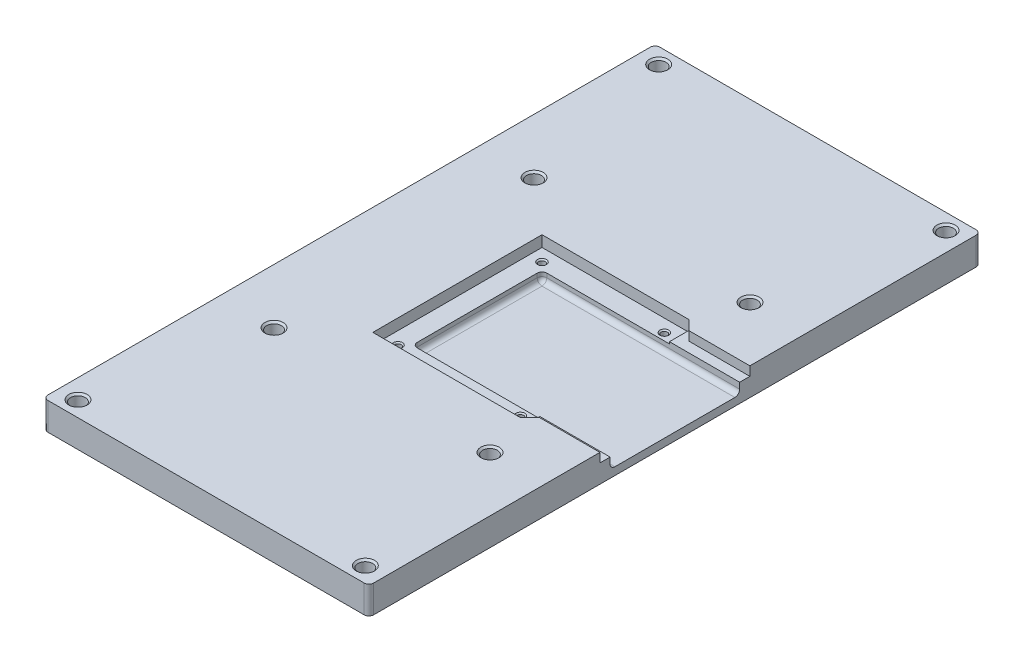
SolidWorks part; units mm, degrees
ref_plane "Front Plane" through (0, 0, 0) normal (0, 0, 1) x (1, 0, 0)
ref_plane "Top Plane" through (0, 0, 0) normal (0, 1, 0) x (1, 0, 0)
ref_plane "Right Plane" through (0, 0, 0) normal (1, 0, 0) x (0, 0, -1)
sketch "Sketch1" plane through (0, 0, 0) normal (0, 1, 0) x (1, 0, 0)
  line L0 (0, -112.5) -> (0, 112.5) construction
  line L1 (67.875, 112.5) -> (-67.875, 112.5) construction
  line L2 (-67.875, 112.5) -> (-67.875, -112.5)
  line L3 (-67.875, 0) -> (67.875, 0) construction
  line L4 (-67.875, 112.5) -> (-67.875, 125.5)
  line L5 (-65.875, 127.5) -> (65.875, 127.5)
  line L6 (0, 127.5) -> (0, 112.5) construction
  line L7 (67.875, 112.5) -> (67.875, 125.5)
  line L8 (67.875, 112.5) -> (67.875, -112.5)
  line L9 (0, -127.5) -> (0, -112.5) construction
  line L10 (67.875, -112.5) -> (-67.875, -112.5) construction
  line L11 (67.875, -112.5) -> (67.875, -125.5)
  line L12 (-65.875, -127.5) -> (65.875, -127.5)
  line L13 (-67.875, -112.5) -> (-67.875, -125.5)
  line L14 (-67.875, 115.5) -> (67.875, 115.5) construction
  circle A1 centre (-59.875, 121) radius 3.075 construction
  circle A2 centre (59.875, 121) radius 3.075 construction
  circle A5 centre (59.875, -121) radius 3.075 construction
  circle A6 centre (-59.875, -121) radius 3.075 construction
  arc A8 (-65.875, -127.5) -> (-67.875, -125.5) centre (-65.875, -125.5) cw
  arc A9 (67.875, -125.5) -> (65.875, -127.5) centre (65.875, -125.5) cw
  arc A10 (67.875, 125.5) -> (65.875, 127.5) centre (65.875, 125.5) ccw
  arc A11 (-67.875, 125.5) -> (-65.875, 127.5) centre (-65.875, 125.5) cw
  circle A12 centre (-45, 54.175) radius 3.075 construction
  circle A13 centre (45, 54.175) radius 3.075 construction
  circle A14 centre (45, -54.175) radius 3.075 construction
  circle A15 centre (-45, -54.175) radius 3.075 construction
  point P24 (0, 0)
  point P36 (-67.875, -127.5)
  point P39 (67.875, -127.5)
  point P42 (67.875, 127.5)
  point P45 (-67.875, 127.5)
  dimension "D5" = 54.175
  dimension "D10" = 2
  dimension "D3" = 6.15
  dimension "D1" = 67.875
  dimension "D2" = 112.5
  dimension "D4" = 6.5
  dimension "D6" = 8
  dimension "D7" = 8.5
  dimension "D8" = 12
  dimension "D9" = 3
  dimension "D11" = 127.5
  dimension "D12" = 45
extrude "Boss-Extrude1" add sketch "Sketch1" along normal blind 11.5
sketch "Sketch3" plane through (0, 11.5, 0) normal (0, 1, 0) x (1, 0, 0)
  line L0 (0, 0) -> (-67.875, 0) construction
  line L1 (-67.875, 125.5) -> (-67.875, -125.5) construction
  line L2 (0, 0) -> (0, 127.5) construction
  line L3 (65.875, 127.5) -> (-65.875, 127.5) construction
  line L4 (3.96, -16.3) -> (3.96, 16.3)
  line L5 (-2.46, -17.8) -> (2.46, -17.8)
  line L6 (-3.96, 16.3) -> (-3.96, -16.3)
  line L7 (2.46, 17.8) -> (-2.46, 17.8)
  line L8 (0, 17.8) -> (0, -17.8) construction
  line L9 (13.25, 0) -> (0, 0) construction
  line L10 (16.15, 10.025) -> (10.35, 10.025)
  line L11 (16.15, 10.025) -> (16.15, -10.025)
  line L12 (16.15, -10.025) -> (10.35, -10.025)
  line L13 (10.35, 10.025) -> (10.35, -10.025)
  line L14 (16.15, 10.025) -> (10.35, -10.025) construction
  line L15 (16.15, -10.025) -> (10.35, 10.025) construction
  line L16 (13.25, 0) -> (13.25, 10.025) construction
  line L17 (-16.15, 10.025) -> (-16.15, -10.025)
  line L18 (-16.15, -10.025) -> (-10.35, -10.025)
  line L23 (-16.15, 10.025) -> (-10.35, 10.025)
  line L24 (-10.35, 10.025) -> (-10.35, -10.025)
  arc A0 (-2.46, 17.8) -> (-3.96, 16.3) centre (-2.46, 16.3) ccw
  arc A1 (3.96, 16.3) -> (2.46, 17.8) centre (2.46, 16.3) ccw
  arc A2 (2.46, -17.8) -> (3.96, -16.3) centre (2.46, -16.3) ccw
  arc A3 (-3.96, -16.3) -> (-2.46, -17.8) centre (-2.46, -16.3) ccw
  point P9 (0, 0)
  point P23 (0, 0)
  dimension "D2" = 1.5
  dimension "D1" = 35.6
  dimension "D3" = 7.92
  dimension "D4" = 20.05
  dimension "D5" = 5.8
  dimension "D6" = 13.25
sketch "Sketch4" plane through (0, 11.5, 0) normal (0, 1, 0) x (1, 0, 0)
  circle A0 centre (-59.875, -121) radius 3.075 construction
  circle A1 centre (59.875, -121) radius 3.075 construction
  circle A2 centre (59.875, 121) radius 3.075 construction
  circle A3 centre (45, -54.175) radius 3.075 construction
  circle A4 centre (-45, -54.175) radius 3.075 construction
  circle A5 centre (-59.875, 121) radius 3.075 construction
  circle A6 centre (45, 54.175) radius 3.075 construction
  circle A7 centre (-45, 54.175) radius 3.075 construction
  circle A8 centre (-59.875, -121) radius 3.075
  circle A9 centre (59.875, -121) radius 3.075
  circle A10 centre (59.875, 121) radius 3.075
  circle A13 centre (-59.875, 121) radius 3.075
  circle A14 centre (45, -54.175) radius 3.075
  circle A15 centre (-45, -54.175) radius 3.075
  circle A16 centre (45, 54.175) radius 3.075
  circle A17 centre (-45, 54.175) radius 3.075
extrude "Cut-Extrude1" cut sketch "Sketch4" against normal blind 6
sketch "Sketch21" plane through (0, 11.5, 0) normal (0, 1, 0) x (1, 0, 0)
  line L0 (38.5, 35) -> (-22.5, 35) construction
  line L1 (38.5, 35) -> (42.5, 31) construction
  line L2 (-22.5, 35) -> (-22.5, -35) construction
  line L3 (-22.5, 0) -> (0, 0) construction
  line L4 (0, 0) -> (38.5, 0) construction
  line L5 (38.5, -35) -> (38.5, 35) construction
  line L6 (38.5, -35) -> (-22.5, -35) construction
  line L7 (42.5, 31) -> (67.875, 31) construction
  line L8 (67.875, -125.5) -> (67.875, 125.5) construction
  line L9 (67.875, 31) -> (67.875, -31)
  line L10 (67.875, 0) -> (38.5, 0) construction
  line L11 (42.5, -31) -> (67.875, -31) construction
  line L12 (38.5, -35) -> (42.5, -31) construction
  line L13 (42.6036, 31.25) -> (67.875, 31.25)
  line L14 (38.6036, 35.25) -> (42.6036, 31.25)
  line L15 (38.6036, 35.25) -> (-22.75, 35.25)
  line L16 (-22.75, 35.25) -> (-22.75, -35.25)
  line L17 (38.6036, -35.25) -> (-22.75, -35.25)
  line L18 (38.6036, -35.25) -> (42.6036, -31.25)
  line L19 (42.6036, -31.25) -> (67.875, -31.25)
  line L20 (67.875, -31.25) -> (67.875, -31)
  line L21 (67.875, 31) -> (67.875, 31.25)
  circle A0 centre (-17.5, 30) radius 1.6 construction
  circle A1 centre (33.5, 30) radius 1.6 construction
  circle A2 centre (33.5, -30) radius 1.6 construction
  circle A3 centre (-17.5, -30) radius 1.6 construction
  dimension "D8" = 3.2
  dimension "D1" = 22.5
  dimension "D2" = 61
  dimension "D3" = 35
  dimension "D4" = 5
  dimension "D5" = 5
  dimension "D6" = 5
  dimension "D7" = 5
  dimension "D9" = 45
  dimension "D10" = 4
  dimension "D12" = 25.375
  dimension "D11" = 0.25
extrude "Cut-Extrude6" cut sketch "Sketch21" against normal blind 4.6
sketch "Sketch24" plane through (0, 6.9, 0) normal (0, 1, 0) x (1, 0, 0)
  line L0 (67.875, 27) -> (-14.5, 27)
  line L2 (-14.5, 27) -> (-14.5, -27)
  line L3 (-14.5, -27) -> (67.875, -27)
  line L4 (67.875, -27) -> (67.875, 27)
  line L8 (38.5, 35) -> (-22.5, 35) construction
  line L10 (-22.5, 35) -> (-22.5, -35) construction
  line L11 (38.5, -35) -> (-22.5, -35) construction
  line L12 (67.875, -31.25) -> (67.875, 31.25) construction
  dimension "D1" = 8
  dimension "D2" = 8
  dimension "D3" = 8
extrude "Cut-Extrude3" cut sketch "Sketch24" against normal blind 3.7 and the other way through all
sketch "Sketch25" plane through (0, 6.9, 0) normal (0, 1, 0) x (1, 0, 0)
  circle A0 centre (33.5, 30) radius 1.35
  circle A1 centre (-17.5, 30) radius 1.35
  circle A2 centre (33.5, -30) radius 1.35
  circle A3 centre (-17.5, -30) radius 1.35
  dimension "D1" = 2.7
extrude "Cut-Extrude4" cut sketch "Sketch25" against normal blind 5
chamfer "Chamfer4" distance 0.5 angle 45 4 edges at (-17.5, 6.9, 31.35) (33.5, 6.9, 31.35) (33.5, 6.9, -28.65) (-17.5, 6.9, -28.65)
fillet "Fillet1" radius 2 5 edges at (26.6875, 3.2, 27) (-14.5, 5.05, 27) (-14.5, 5.05, -27) (-14.5, 3.2, 0) (26.6875, 3.2, -27)
sketch "Sketch26" plane through (0, 6.9, 0) normal (0, 1, 0) x (1, 0, 0)
  line L0 (0, 0) -> (67.875, 0) construction
  line L1 (67.875, -25) -> (67.875, 25) construction
  line L2 (38.6036, 35.25) -> (38.6036, 27)
  line L3 (67.875, 27) -> (-12.5, 27) construction
  line L4 (38.6036, 27) -> (67.875, 27)
  line L5 (67.875, 27) -> (67.875, 31.25)
  line L6 (67.875, 31.25) -> (42.6036, 31.25)
  line L7 (42.6036, 31.25) -> (38.6036, 35.25)
  line L8 (42.6036, -31.25) -> (38.6036, -35.25)
  line L9 (67.875, -31.25) -> (42.6036, -31.25)
  line L10 (67.875, -27) -> (67.875, -31.25)
  line L11 (38.6036, -27) -> (67.875, -27)
  line L12 (38.6036, -35.25) -> (38.6036, -27)
extrude "Boss-Extrude2" add sketch "Sketch26" along normal blind 0.8
chamfer "Chamfer5" distance 0.75 angle 45 8 edges at (59.875, 11.5, 124.075) (-59.875, 11.5, 124.075) (-59.875, 11.5, -117.925) (59.875, 11.5, -117.925) (-45, 11.5, 57.25) (45, 11.5, 57.25) (45, 11.5, -51.1) (-45, 11.5, -51.1)
equation "\"D5@Sketch21\"=\"D4@Sketch21\""
equation "\"D6@Sketch21\"=\"D4@Sketch21\""
equation "\"D7@Sketch21\"=\"D4@Sketch21\""
equation "\"D2@Sketch24\"=\"D1@Sketch24\""
equation "\"D3@Sketch24\"=\"D1@Sketch24\""
